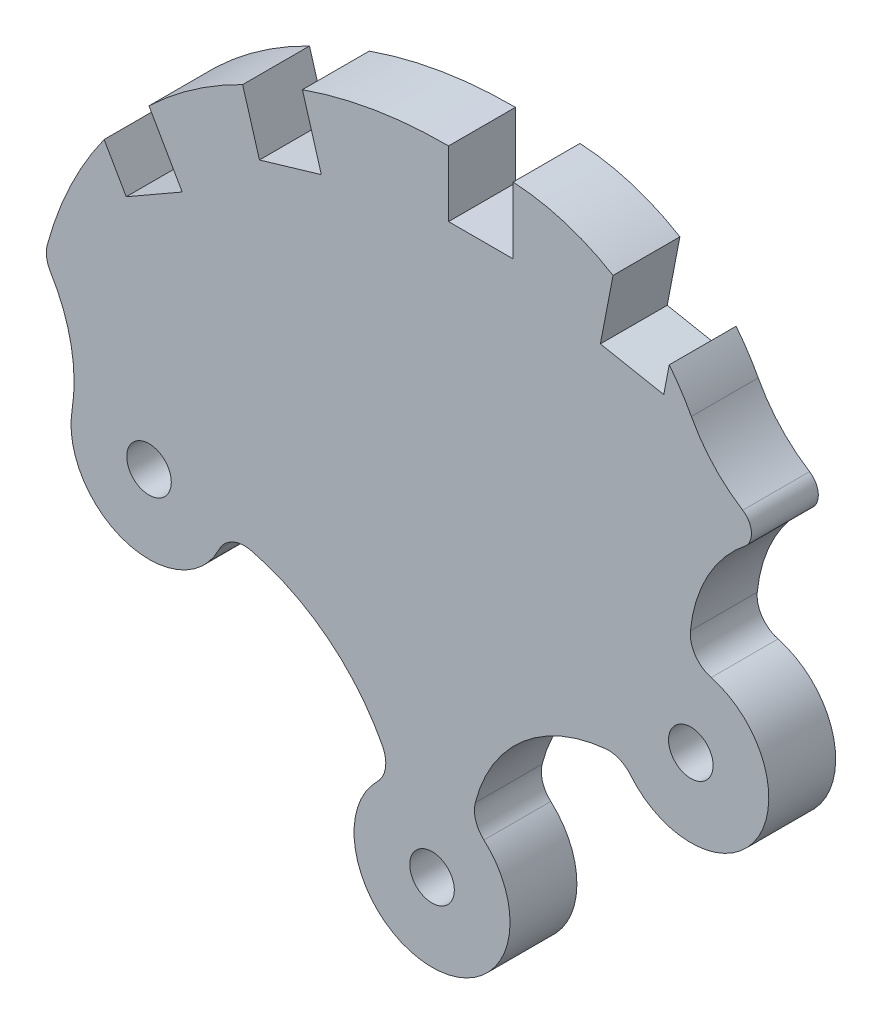
SolidWorks part; units mm, degrees
material "Acrylic (Medium-high impact)"
ref_plane "Front Plane" through (0, 0, 0) normal (0, 0, 1) x (1, 0, 0)
ref_plane "Top Plane" through (0, 0, 0) normal (0, 1, 0) x (1, 0, 0)
ref_plane "Right Plane" through (0, 0, 0) normal (1, 0, 0) x (0, 0, -1)
sketch "스케치1" plane through (0, 0, 0) normal (0, 0, 1) x (1, 0, 0)
  line L0 (9.9447, -1.0375) -> (9.2984, -2.3717) construction
  line L1 (9.2984, -2.3717) -> (9.2624, -3.8538) construction
  line L2 (0.3889, -9.2217) -> (0, -9.2) construction
  line L3 (0, -9.2) -> (-0.3889, -9.2217) construction
  line L4 (0, -9.2) -> (0, 0) construction
  line L5 (9.9447, -1.0375) -> (-9.9447, -1.0375) construction
  line L6 (9.9447, -1.0375) -> (9.2624, -3.8538) construction
  line L7 (10.6897, -4.1762) -> (-10.7811, -4.1762) construction
  line L9 (1.7841, -9.6889) -> (-1.7841, -9.6889) construction
  arc A0 (-9.9447, -1.0375) -> (9.9447, -1.0375) centre (0, -48.1789) cw construction
  arc A1 (-9.2624, -3.8538) -> (9.2624, -3.8538) centre (0, -48.1789) cw construction
  circle A2 centre (-12.7, -3.1959) radius 3.5 construction
  circle A3 centre (12.7, -3.1959) radius 3.5 construction
  arc A4 (-12.7, -3.1959) -> (12.7, -3.1959) centre (0, -48.1789) cw construction
  circle A5 centre (-12.7, -3.1959) radius 1
  circle A6 centre (12.7, -3.1959) radius 1 construction
  circle A7 centre (0, -12.7) radius 3.5 construction
  circle A8 centre (0, -12.7) radius 1
  arc A12 (10.6897, -4.1762) -> (9.2624, -3.8538) centre (0, -48.1789) cw construction
  arc A17 (-11.2738, 0.0003) -> (-9.2624, -3.8538) centre (-12.7, -3.1959) ccw construction
  arc A26 (-17.4047, 2.6892) -> (-7.899, 14.1326) centre (-1.2139, -1.0902) cw
  arc A30 (1.7841, 16.0582) -> (-7.899, 14.1326) centre (0.6209, -3.4023) ccw
  arc A35 (-16.1547, -2.6347) -> (-9.2624, -3.8538) centre (-12.7, -3.1959) ccw
  arc A36 (1.7841, 16.0582) -> (11.6363, 11.0257) centre (3.1176, 6.5085) cw
  arc A37 (11.6363, 11.0257) -> (13.9398, 8.5344) centre (17.4955, 14.1326) ccw
  arc A39 (11.6363, 0.1385) -> (9.2624, -3.8538) centre (12.7, -3.1959) cw construction
  arc A41 (9.2665, -3.8368) -> (9.259, -3.8358) centre (8.4137, -10.4559) ccw
  arc A42 (-1.7841, -9.6889) -> (1.7841, -9.6889) centre (0, -12.7) ccw
  arc A45 (-17.4047, 2.6892) -> (-16.1547, -2.6347) centre (-23.2253, -1.4861) cw
  arc A47 (13.9398, 8.5344) -> (14.1291, 7.2674) centre (13.4853, 7.8188) cw
  arc A48 (14.1291, 7.2674) -> (11.5838, 1.4466) centre (18.2143, 2.0141) ccw
  arc A49 (12.1211, -0.6614) -> (11.6363, 0.1385) centre (8.917, -2.0565) ccw construction
  arc A50 (12.1211, -0.6614) -> (10.6897, -4.1762) centre (14.1291, -3.5281) cw construction
  circle A51 centre (14.1291, -3.5281) radius 1 construction
  arc A52 (-9.2624, -3.8538) -> (-1.7841, -9.6889) centre (-10.3142, -12.9114) cw
  arc A53 (8.5686, -3.7839) -> (11.5838, 1.4466) centre (11.6108, -2.0533) ccw
  circle A54 centre (11.6108, -2.0533) radius 1
  arc A55 (8.5686, -3.7839) -> (1.7841, -9.6889) centre (8.4137, -10.4559) ccw
  arc A56 (12.1154, -0.6484) -> (12.1211, -0.6614) centre (18.2143, 2.0141) ccw
  dimension "D1" = 2
  dimension "D2" = 2.5
  dimension "D3" = 12.7
  dimension "D6" = 2.5
  dimension "D5" = 25.4
extrude "보스-돌출1" add sketch "스케치1" along normal blind 3
fillet "필렛2" radius 0.508 1 edges at (14.1291, 7.2674, 1.5)
fillet "필렛3" radius 1.27 6 edges at (8.5686, -3.7839, 1.5) (-9.2624, -3.8538, 1.5) (1.7841, -9.6889, 1.5) (-1.7841, -9.6889, 1.5) (-17.4047, 2.6892, 1.5) (11.5838, 1.4466, 1.5)
sketch "스케치3" plane through (0, 0, 3) normal (0, 0, 1) x (1, 0, 0)
  line L0 (-4.9186, -5.5606) -> (-13.9584, 10.2079) construction
  line L1 (-1.1545, -5.9203) -> (-7.7107, 16.3015) construction
  line L2 (2.1886, -4.8754) -> (2.1886, 17.4181) construction
  line L3 (5.9318, -4.2608) -> (9.3592, 13.524) construction
  line L4 (-13.7222, 6.8854) -> (-11.2106, 8.3252)
  line L5 (-13.7222, 6.8854) -> (-15.2142, 9.488)
  line L6 (-11.2106, 8.3252) -> (-12.7027, 10.9279)
  line L7 (-15.2142, 9.488) -> (-12.7027, 10.9279)
  line L8 (-13.7222, 6.8854) -> (-12.7027, 10.9279) construction
  line L9 (-11.2106, 8.3252) -> (-15.2142, 9.488) construction
  line L10 (-7.745, 11.3025) -> (-4.9684, 12.1217)
  line L11 (-7.745, 11.3025) -> (-8.594, 14.1799)
  line L12 (-4.9684, 12.1217) -> (-5.8173, 14.9991)
  line L13 (-8.594, 14.1799) -> (-5.8173, 14.9991)
  line L14 (-7.745, 11.3025) -> (-5.8173, 14.9991) construction
  line L15 (-4.9684, 12.1217) -> (-8.594, 14.1799) construction
  line L16 (0.7411, 13.1508) -> (3.6361, 13.1508)
  line L17 (0.7411, 13.1508) -> (0.7411, 16.1508)
  line L18 (3.6361, 13.1508) -> (3.6361, 16.1508)
  line L19 (0.7411, 16.1508) -> (3.6361, 16.1508)
  line L20 (0.7411, 13.1508) -> (3.6361, 16.1508) construction
  line L21 (3.6361, 13.1508) -> (0.7411, 16.1508) construction
  line L22 (7.5537, 11.805) -> (10.3964, 11.2572)
  line L23 (7.5537, 11.805) -> (8.1214, 14.7508)
  line L24 (10.3964, 11.2572) -> (10.9641, 14.203)
  line L25 (8.1214, 14.7508) -> (10.9641, 14.203)
  line L26 (7.5537, 11.805) -> (10.9641, 14.203) construction
  line L27 (10.3964, 11.2572) -> (8.1214, 14.7508) construction
  arc A0 (-2.2182, -8.7159) -> (-8.11, -4.0633) centre (-10.3142, -12.9114) ccw construction
  arc A1 (1.7841, 16.0582) -> (-7.899, 14.1326) centre (0.6209, -3.4023) ccw construction
  arc A2 (7.8037, -3.81) -> (1.9413, -8.8287) centre (8.4137, -10.4559) ccw construction
  arc A3 (11.6363, 11.0257) -> (1.7841, 16.0582) centre (3.1176, 6.5085) ccw construction
  arc A4 (-7.899, 14.1326) -> (-17.2622, 3.2547) centre (-1.2139, -1.0902) ccw construction
  point P9 (-13.2124, 8.9066)
  point P10 (-6.7812, 13.1508)
  point P11 (2.1886, 14.6508)
  point P12 (9.2589, 13.004)
  dimension "D1" = 2.895
  dimension "D2" = 3
extrude "컷-돌출1" cut sketch "스케치3" against normal blind 3
